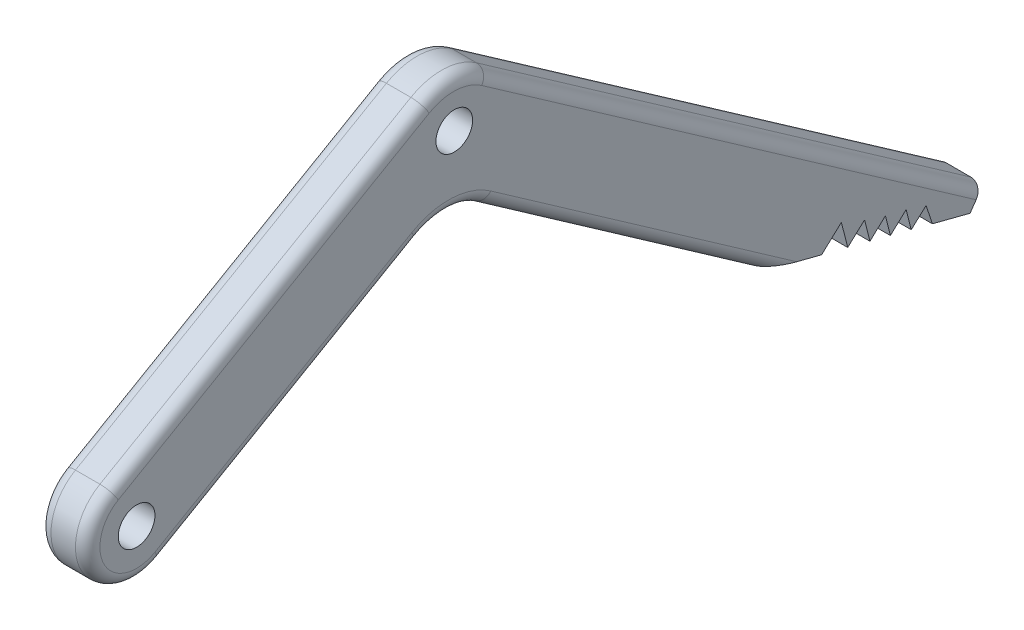
SolidWorks part; units mm, degrees
ref_plane "Front Plane" through (0, 0, 0) normal (0, 0, 1) x (1, 0, 0)
ref_plane "Top Plane" through (0, 0, 0) normal (0, 1, 0) x (1, 0, 0)
ref_plane "Right Plane" through (0, 0, 0) normal (1, 0, 0) x (0, 0, -1)
sketch "Sketch1" plane through (0, 0, 0) normal (1, 0, 0) x (0, 0, -1)
  line L0 (0, 0) -> (25.9808, 15) construction
  line L1 (25.9808, 15) -> (66.9384, -13.6788) construction
  line L2 (2, -3.4641) -> (23.0153, 8.6691)
  line L3 (28.3832, 8.4347) -> (51.2327, -7.5647)
  line L4 (-2, 3.4641) -> (23.429, 18.1456)
  line L5 (28.7969, 17.9112) -> (69.2327, -10.4022)
  line L6 (0, 0) -> (62.7261, 0) construction
  line L12 (25.7739, 10.2618) -> (64.6441, -16.9554) construction
  line L13 (2, -3.4641) -> (25.7739, 10.2618) construction
  line L14 (-2, 3.4641) -> (26.1876, 19.7382) construction
  line L15 (26.1876, 19.7382) -> (69.2327, -10.4022) construction
  line L17 (65.081, -11.1343) -> (64.5675, -9.5815)
  line L18 (64.5675, -9.5815) -> (63.3509, -10.6883)
  line L19 (63.3509, -10.6883) -> (62.935, -9.051)
  line L20 (62.935, -9.051) -> (61.6482, -10.2494)
  line L21 (61.6482, -10.2494) -> (61.2399, -8.6421)
  line L22 (61.2399, -8.6421) -> (59.9767, -9.8186)
  line L23 (59.9767, -9.8186) -> (59.5342, -8.0771)
  line L24 (59.5342, -8.0771) -> (58.1568, -9.3495)
  line L25 (58.1568, -9.3495) -> (57.6381, -7.3076)
  line L26 (57.6381, -7.3076) -> (56.0231, -8.7995)
  line L27 (56.0231, -8.7995) -> (51.2327, -7.5647)
  line L28 (65.081, -11.1343) -> (68.1637, -11.9289)
  line L29 (68.1637, -11.9289) -> (69.2327, -10.4022)
  arc A0 (2, -3.4641) -> (-2, 3.4641) centre (0, 0) cw
  circle A2 centre (0, 0) radius 1.5
  circle A3 centre (25.9808, 15) radius 1.5
  arc A4 (23.0153, 8.6691) -> (28.3832, 8.4347) centre (25.5153, 4.339) cw
  arc A5 (23.429, 18.1456) -> (28.7969, 17.9112) centre (25.929, 13.8154) cw
  dimension "D7" = 3
  dimension "D11" = 5
  dimension "D3" = 30
  dimension "D4" = 115
  dimension "D5" = 50
  dimension "D6" = 30
  dimension "D9" = 18
  dimension "D1" = 4
  dimension "D2" = 4
extrude "Boss-Extrude1" add sketch "Sketch1" along normal blind 4
fillet "Fillet1" radius 1 14 edges at (0, 0.435, -39.8079) (0, 9.3342, -25.7334) (0, 2.6025, -12.5076) (0, -2, 3.4641) (0, 10.8048, -10.7145) (0, 18.8107, -26.1471) (4, 0.435, -39.8079) (4, 9.3342, -25.7334) (4, 2.6025, -12.5076) (4, -2, 3.4641) (4, 10.8048, -10.7145) (4, 18.8107, -26.1471) (0, 3.7545, -49.0148) (4, 3.7545, -49.0148)
